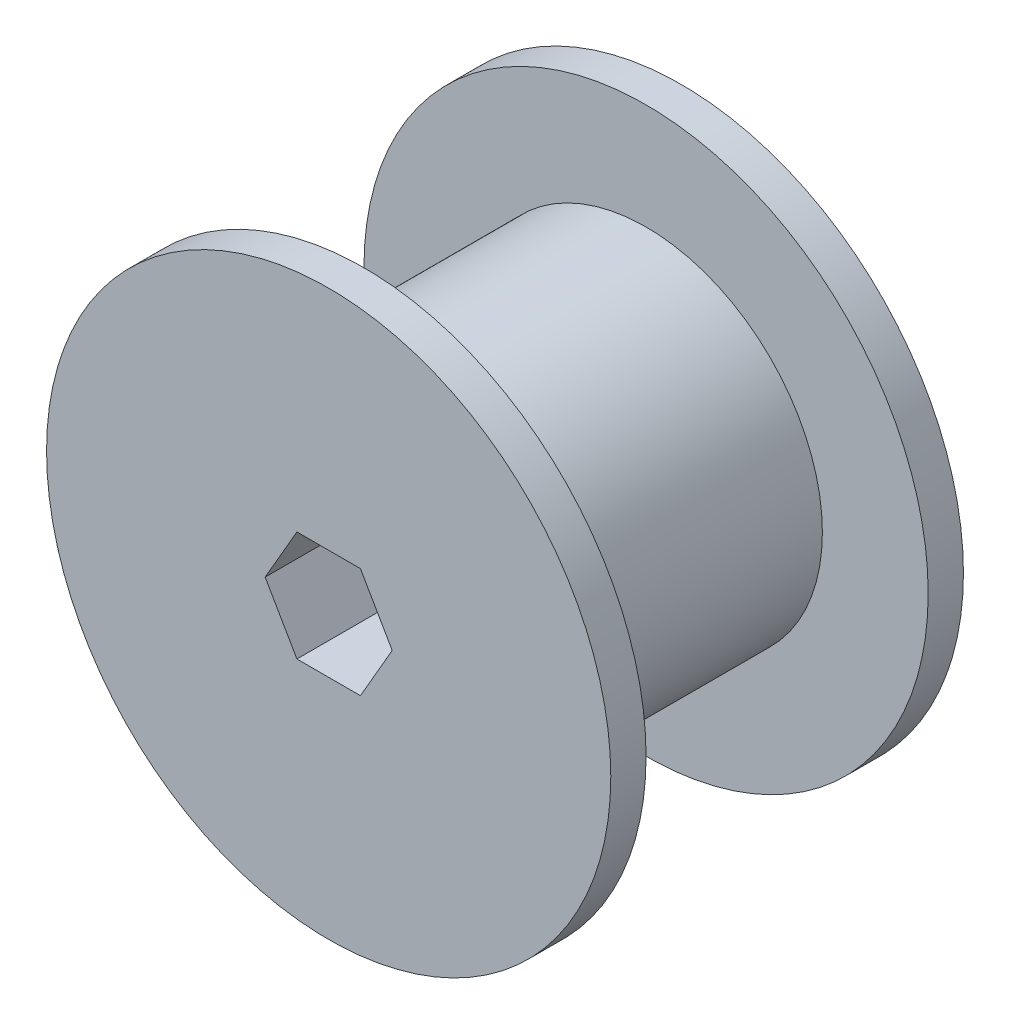
SolidWorks part; units mm, degrees
ref_plane "Front Plane" through (0, 0, 0) normal (0, 0, 1) x (1, 0, 0)
ref_plane "Top Plane" through (0, 0, 0) normal (0, 1, 0) x (1, 0, 0)
ref_plane "Right Plane" through (0, 0, 0) normal (1, 0, 0) x (0, 0, -1)
sketch "Sketch1" plane through (0, 0, 0) normal (0, 0, 1) x (1, 0, 0)
  circle A0 centre (0, 0) radius 15.875
extrude "Drum" add sketch "Sketch1" along normal mid plane 25.4
sketch "Sketch3" plane through (0, 0, 12.7) normal (0, 0, 1) x (1, 0, 0)
  circle A0 centre (0, 0) radius 25.4
extrude "Flange" add sketch "Sketch3" along normal blind 3.175
mirror "Flange2" about plane through (0, 0, 0) normal (0, 0, 1) of "Flange"
sketch "Sketch4" plane through (0, 0, 15.875) normal (0, 0, 1) x (1, 0, 0)
  line L1 (5.7192, 0) -> (2.8596, 4.953)
  line L2 (2.8596, 4.953) -> (-2.8596, 4.953)
  line L3 (-2.8596, 4.953) -> (-5.7192, 0)
  line L4 (-5.7192, 0) -> (-2.8596, -4.953)
  line L5 (-2.8596, -4.953) -> (2.8596, -4.953)
  line L6 (2.8596, -4.953) -> (5.7192, 0)
  circle A0 centre (0, 0) radius 4.953 construction
extrude "Attachment" cut sketch "Sketch4" against normal through all
